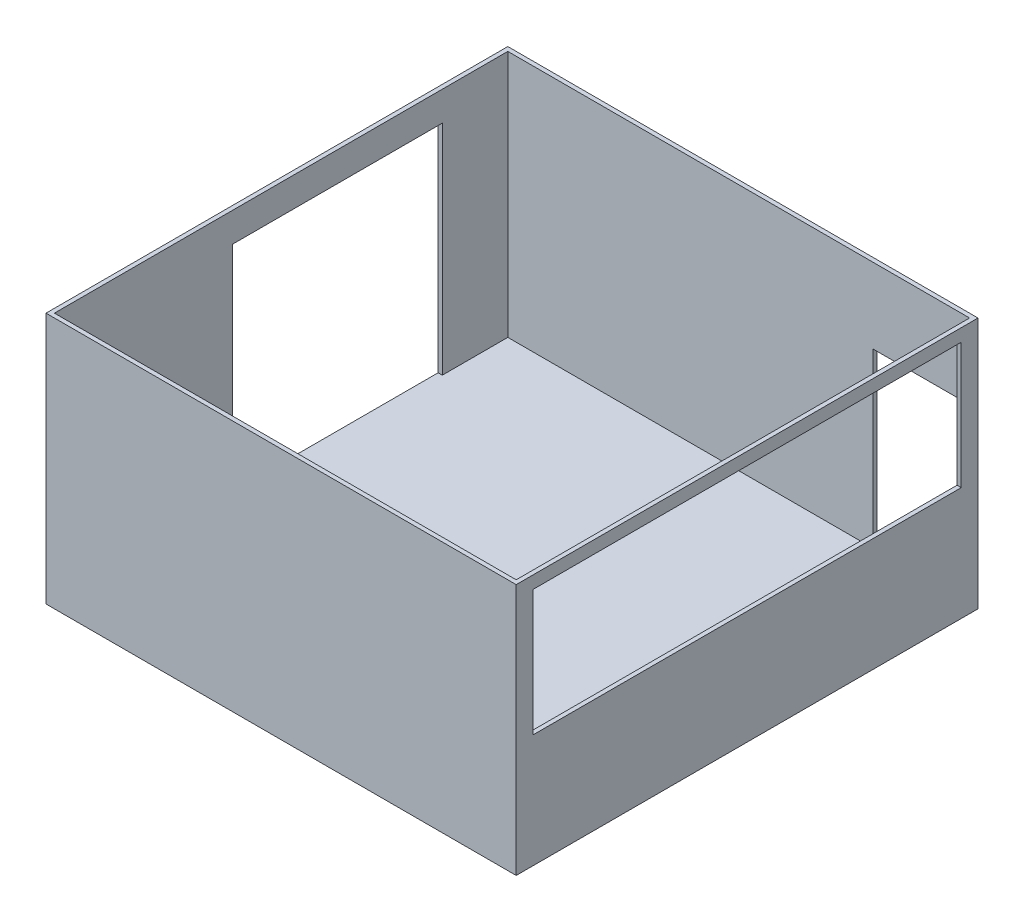
SolidWorks part; units mm, degrees
ref_plane "Front Plane" through (0, 0, 0) normal (0, 0, 1) x (1, 0, 0)
ref_plane "Top Plane" through (0, 0, 0) normal (0, 1, 0) x (1, 0, 0)
ref_plane "Right Plane" through (0, 0, 0) normal (1, 0, 0) x (0, 0, -1)
sketch "Sketch3" plane through (0, 0, 0) normal (0, 0, 1) x (1, 0, 0)
  line L1 (2800, -1500) -> (-2800, -1500)
  line L2 (2800, -1500) -> (2800, 1500)
  line L3 (2800, 1500) -> (-2800, 1500)
  line L4 (-2800, -1500) -> (-2800, 1500)
  line L5 (2800, -1500) -> (-2800, 1500) construction
  line L6 (2800, 1500) -> (-2800, -1500) construction
  point P0 (0, 0)
  dimension "D1" = 3000
  dimension "D2" = 5600
extrude "Boss-Extrude2" add sketch "Sketch3" along normal blind 5500
shell "Shell2" thickness 50
sketch "Sketch4" plane through (-2800, 0, 0) normal (-1, 0, 0) x (0, 0, 1)
  line L2 (830, -1450) -> (830, 1150)
  line L3 (830, 1150) -> (3330, 1150)
  line L4 (3330, -1450) -> (3330, 1150)
  line L5 (877.1698, -1450) -> (3330, 1150) construction
  line L6 (830, 1150) -> (3330, -1500) construction
  line L7 (0, -1500) -> (0, 1500) construction
  line L8 (830, -1450) -> (3330, -1450)
  point P4 (2080, -175)
  dimension "D1" = 830
  dimension "D3" = 2500
extrude "Cut-Extrude4" cut sketch "Sketch4" against normal blind 3500 contours L4 L3 L2 L8
sketch "Sketch5" plane through (0, 0, 50) normal (0, 0, 1) x (1, 0, 0)
  line L0 (2800, -1500) -> (-2800, -1500) construction
  line L1 (1600, 605) -> (2700, 605)
  line L2 (1600, 605) -> (1600, -1495)
  line L3 (1600, -1495) -> (2700, -1495)
  line L4 (2700, 605) -> (2700, -1495)
  line L5 (1600, 605) -> (2700, -1495) construction
  line L6 (1600, -1495) -> (2700, 605) construction
  line L7 (2750, -1450) -> (2750, 1500) construction
  point P4 (2150, -445)
  dimension "D1" = 1100
  dimension "D2" = 2100
  dimension "D3" = 5
  dimension "D4" = 50
extrude "Cut-Extrude6" cut sketch "Sketch5" against normal through all
sketch "Sketch6" plane through (2750, 0, 0) normal (-1, 0, 0) x (0, 0, 1)
  line L4 (5450, 1350) -> (5450, -150)
  line L6 (5300, -150) -> (200, -150)
  line L7 (5450, -1450) -> (5450, 1500) construction
  line L9 (5300, -150) -> (5300, 1350)
  line L10 (5300, 1350) -> (200, 1350)
  line L11 (200, -150) -> (200, 1350)
  line L12 (5300, -150) -> (200, 1350) construction
  line L13 (5300, 1350) -> (200, -150) construction
  line L14 (50, -1450) -> (50, 1500) construction
  line L15 (5450, 1500) -> (50, 1500) construction
  point P0 (2750, 600)
  point P4 (2750, 600)
  dimension "D1" = 1500
  dimension "D2" = 150
  dimension "D3" = 150
  dimension "D4" = 5100
  dimension "D5" = 1500
  dimension "D6" = 150
extrude "Cut-Extrude7" cut sketch "Sketch6" against normal through all contours L11 L6 L9 L10
